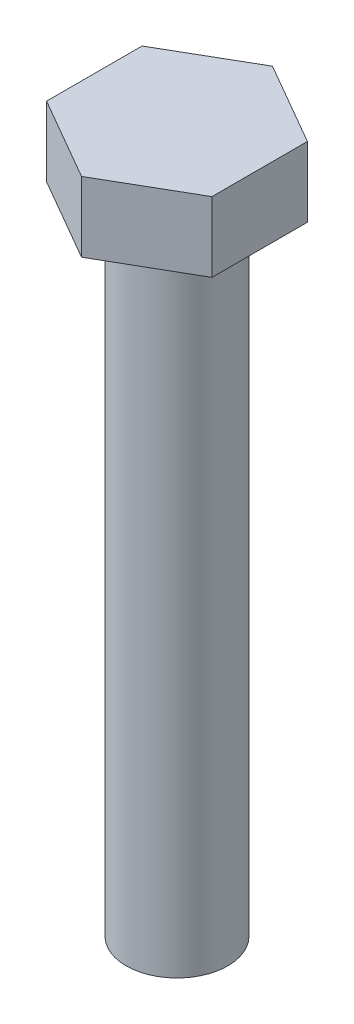
SolidWorks part; units mm, degrees
material "Acier allié"
ref_plane "Plan de face" through (0, 0, 0) normal (0, 0, 1) x (1, 0, 0)
ref_plane "Plan de dessus" through (0, 0, 0) normal (0, 1, 0) x (1, 0, 0)
ref_plane "Plan de droite" through (0, 0, 0) normal (1, 0, 0) x (0, 0, -1)
sketch "Esquisse1" plane through (0, 0, 0) normal (0, 1, 0) x (1, 0, 0)
  line L1 (6.5, 3.7528) -> (0, 7.5056)
  line L2 (0, 7.5056) -> (-6.5, 3.7528)
  line L3 (-6.5, 3.7528) -> (-6.5, -3.7528)
  line L4 (-6.5, -3.7528) -> (0, -7.5056)
  line L5 (0, -7.5056) -> (6.5, -3.7528)
  line L6 (6.5, -3.7528) -> (6.5, 3.7528)
  circle A0 centre (0, 0) radius 6.5 construction
  dimension "D1" = 13
extrude "Boss.-Extru.1" add sketch "Esquisse1" along normal blind 5.5
sketch "Esquisse2" plane through (0, 0, 0) normal (0, 1, 0) x (1, 0, 0)
  circle A0 centre (0, 0) radius 4
  dimension "D1" = 8
extrude "Boss.-Extru.2" add sketch "Esquisse2" against normal blind 50
